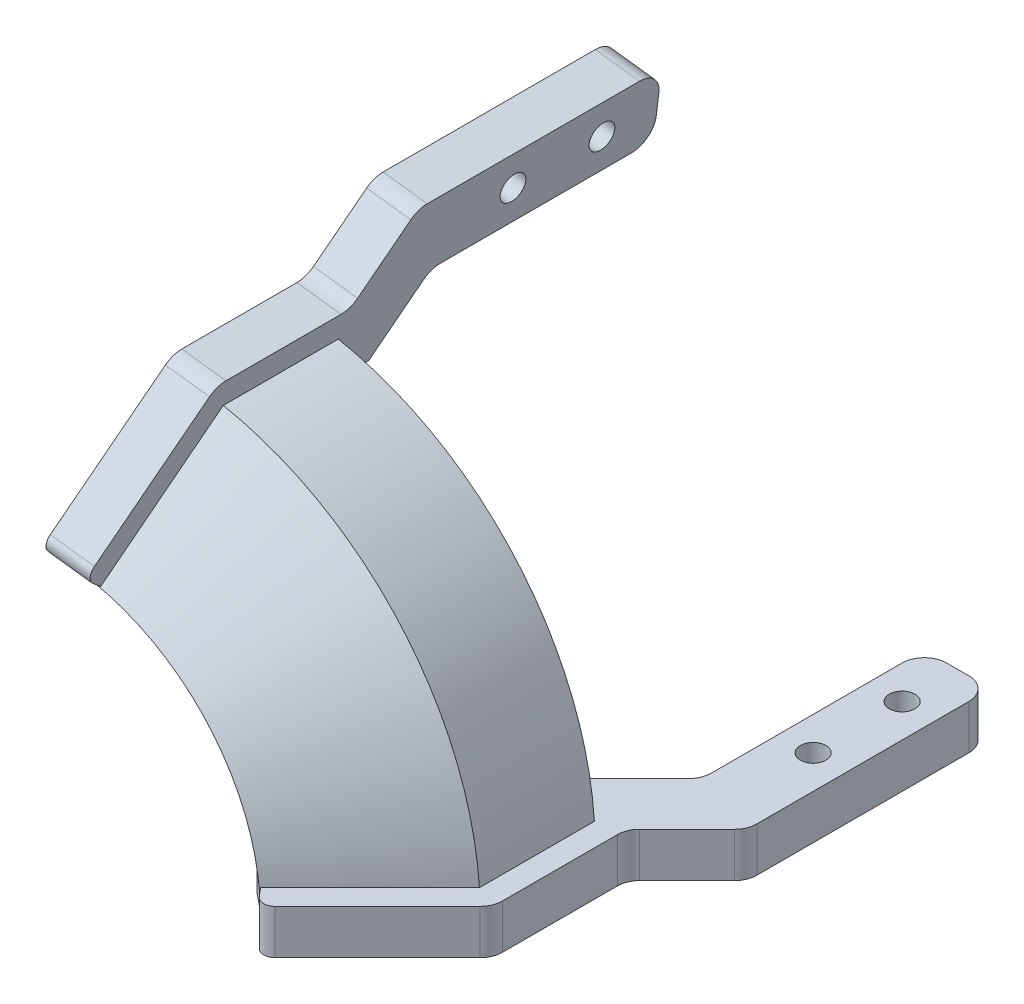
SolidWorks part; units mm, degrees
material "聚脂树脂"
ref_plane "前视基准面" through (0, 0, 0) normal (0, 0, 1) x (1, 0, 0)
ref_plane "上视基准面" through (0, 0, 0) normal (0, 1, 0) x (1, 0, 0)
ref_plane "右视基准面" through (0, 0, 0) normal (1, 0, 0) x (0, 0, -1)
other "Configuration Table"
sketch "草图1" plane through (0, 0, 0) normal (0, 1, 0) x (1, 0, 0)
  line L0 (0, 0) -> (0, 40.389) construction
  line L1 (0, 0) -> (49.8304, 0) construction
  line L2 (0, 35) -> (25, 35) construction
  line L3 (25, 35) -> (25, 30) construction
  line L4 (15, 20) -> (25, 30)
  line L5 (25, 30) -> (15, 20) construction
  line L6 (25, -30) -> (15, -20) construction
  line L7 (25, 30) -> (25, 40)
  line L8 (25, -35) -> (25, -30) construction
  line L9 (0, -35) -> (25, -35) construction
  line L10 (0, 35) -> (0, -35) construction
  line L12 (30.5635, 25.664) -> (30.5635, 37.664)
  line L13 (30.5635, 25.664) -> (19.9569, 15.0574)
  line L14 (25, 40) -> (30, 45)
  line L17 (30.5635, 37.664) -> (36, 43.1005)
  line L18 (30, 45) -> (30, 65)
  line L19 (30, 65) -> (36, 65)
  line L20 (36, 65) -> (36, 43.1005)
  line L21 (33, 65) -> (33, 39.979) construction
  arc A0 (15, -20) -> (15, 20) centre (0, 0) ccw construction
  arc A1 (15, 20) -> (19.9569, 15.0574) centre (0, 0) cw
  circle A4 centre (33, 60) radius 1.15
  circle A5 centre (33, 52) radius 1.15
  dimension "D3" = 50
  dimension "D11" = 0
  dimension "D12" = 20
  dimension "D13" = 2.3
  dimension "D14" = 2.3
  dimension "D15" = 8
  dimension "D16" = 5
  dimension "D1" = 5
  dimension "D2" = 25
  dimension "D4" = 35
  dimension "D5" = 45
  dimension "D6" = 7
  dimension "D7" = 135
  dimension "D8" = 10
  dimension "D9" = 5
  dimension "D10" = 6
  dimension "D18" = 15
  dimension "D19" = 12
extrude "凸台-拉伸1" add sketch "草图1" along normal blind 4
fillet "圆角1" radius 2 6 edges at (30.5635, 2, -25.664) (30.5635, 2, -37.664) (30, 2, -45) (36, 2, -43.1005) (36, 2, -65) (30, 2, -65)
fillet "圆角2" radius 1 1 edges at (19.9569, 2, -15.0574)
ref_plane "基准面1" through (0, 2, 0) normal (0, 1, 0) x (1, 0, 0)
ref_axis "基准轴1" through (0, 2, -67.472) along (0, 0, 1)
sketch "草图2" plane through (0, 2, 0) normal (0, 1, 0) x (1, 0, 0)
  line L0 (30.5635, 36.8355) -> (25, 36.8355)
  line L1 (28.5635, 26.4924) -> (28.5635, 36.8355)
  line L2 (28.5635, 26.4924) -> (18.6828, 16.6118)
  line L9 (20.7517, 15.8523) -> (29.9777, 25.0782)
  line L10 (30.5635, 26.4924) -> (30.5635, 36.8355)
  line L11 (31.1492, 38.2497) -> (35.4142, 42.5147)
  line L12 (36, 43.9289) -> (36, 63)
  line L13 (34, 65) -> (32, 65)
  line L14 (30, 63) -> (30, 45.8284)
  line L15 (29.4142, 44.4142) -> (25, 40)
  line L16 (25, 40) -> (25, 30)
  line L17 (25, 30) -> (15, 20)
  line L18 (20.7517, 15.8523) -> (29.9777, 25.0782)
  line L19 (30.5635, 26.4924) -> (30.5635, 36.8355)
  line L20 (31.1492, 38.2497) -> (35.4142, 42.5147)
  line L21 (36, 43.9289) -> (36, 63)
  line L22 (34, 65) -> (32, 65)
  line L23 (30, 63) -> (30, 45.8284)
  line L24 (29.4142, 44.4142) -> (25, 40)
  line L25 (25, 40) -> (25, 30)
  line L26 (25, 30) -> (15, 20)
  arc A9 (19.2737, 15.9225) -> (15, 20) centre (0, 0) ccw
  arc A10 (19.2737, 15.9225) -> (20.7517, 15.8523) centre (20.0446, 16.5594) ccw
  arc A11 (29.9777, 25.0782) -> (30.5635, 26.4924) centre (28.5635, 26.4924) ccw
  arc A12 (31.1492, 38.2497) -> (30.5635, 36.8355) centre (32.5635, 36.8355) ccw
  arc A13 (35.4142, 42.5147) -> (36, 43.9289) centre (34, 43.9289) ccw
  arc A14 (36, 63) -> (34, 65) centre (34, 63) ccw
  arc A15 (32, 65) -> (30, 63) centre (32, 63) ccw
  arc A16 (29.4142, 44.4142) -> (30, 45.8284) centre (28, 45.8284) ccw
  arc A18 (19.2737, 15.9225) -> (15, 20) centre (0, 0) ccw
  arc A19 (19.2737, 15.9225) -> (20.7517, 15.8523) centre (20.0446, 16.5594) ccw
  arc A20 (29.9777, 25.0782) -> (30.5635, 26.4924) centre (28.5635, 26.4924) ccw
  arc A21 (31.1492, 38.2497) -> (30.5635, 36.8355) centre (32.5635, 36.8355) ccw
  arc A22 (35.4142, 42.5147) -> (36, 43.9289) centre (34, 43.9289) ccw
  arc A23 (36, 63) -> (34, 65) centre (34, 63) ccw
  arc A24 (32, 65) -> (30, 63) centre (32, 63) ccw
  arc A25 (29.4142, 44.4142) -> (30, 45.8284) centre (28, 45.8284) ccw
  dimension "D1" = 0
revolve "旋转2" add sketch "草图2" angle 83 about axis through (0, 2, -67.472) along (0, 0, 1)
pattern_circular "阵列(圆周)4" count 2 over 83 about axis through (0, 2, 0) along (0, 0, 1) of "凸台-拉伸1", "圆角1", "圆角2"
